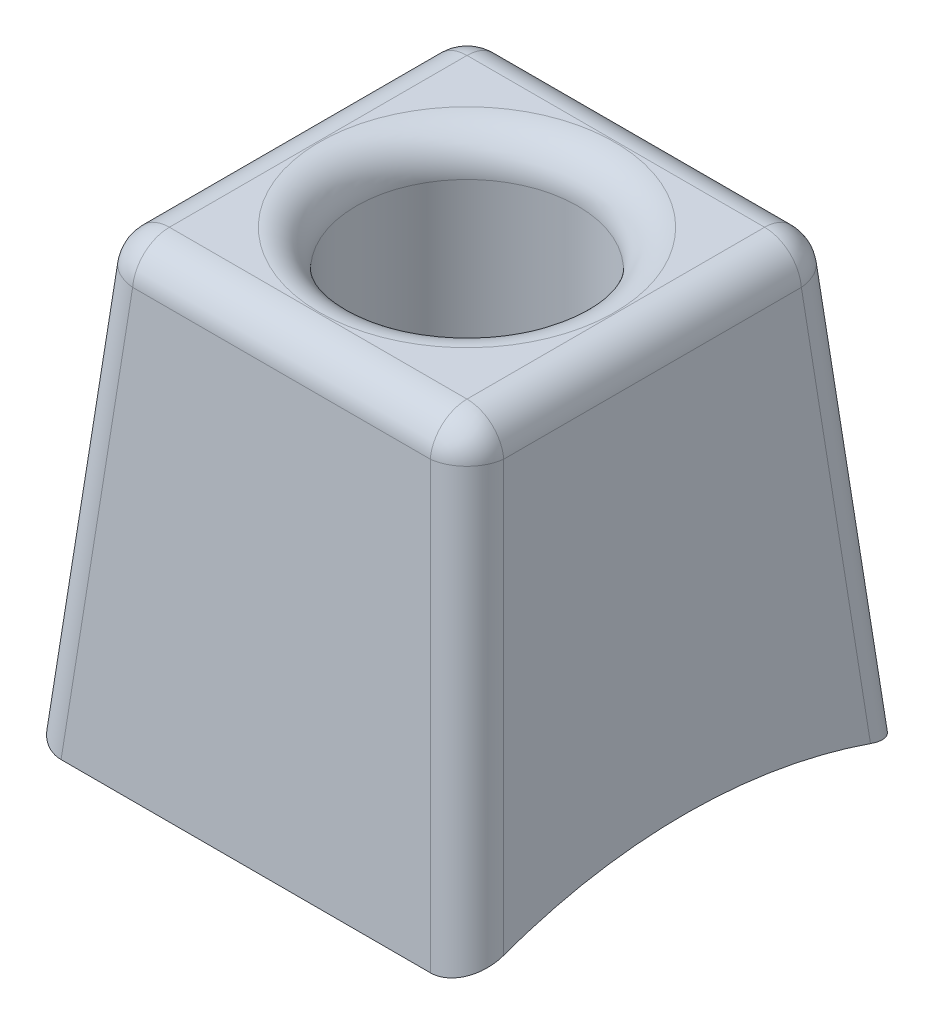
SolidWorks part; units mm, degrees
ref_plane "Front Plane" through (0, 0, 0) normal (0, 0, 1) x (1, 0, 0)
ref_plane "Top Plane" through (0, 0, 0) normal (0, 1, 0) x (1, 0, 0)
ref_plane "Right Plane" through (0, 0, 0) normal (1, 0, 0) x (0, 0, -1)
sketch "Sketch1" plane through (0, 0, 0) normal (0, 1, 0) x (1, 0, 0)
  line L1 (0, 0) -> (-12, 0)
  line L2 (0, 0) -> (0, 12)
  line L3 (0, 12) -> (-12, 12)
  line L4 (-12, 0) -> (-12, 12)
  dimension "D1" = 12
  dimension "D2" = 12
extrude "Boss-Extrude1" add sketch "Sketch1" along normal blind 12 draft 5
sketch "Sketch2" plane through (0, 12, 0) normal (0, 1, 0) x (1, 0, 0)
  line L0 (-10.9501, 6) -> (-1.0499, 6) construction
  line L1 (-10.9501, 10.9501) -> (-10.9501, 1.0499) construction
  line L2 (-1.0499, 1.0499) -> (-1.0499, 10.9501) construction
  line L3 (-6, 10.9501) -> (-6, 1.0499) construction
  line L4 (-1.0499, 10.9501) -> (-10.9501, 10.9501) construction
  line L5 (-10.9501, 1.0499) -> (-1.0499, 1.0499) construction
  circle A0 centre (-6, 6) radius 3
  dimension "D1" = 6
extrude "Cut-Extrude1" cut sketch "Sketch2" against normal through all
fillet "Fillet1" radius 1 9 edges at (-6, 12, -3) (-11.4751, 6, -11.4751) (-0.5249, 6, -11.4751) (-0.5249, 6, -0.5249) (-11.4751, 6, -0.5249) (-6, 12, -10.9501) (-10.9501, 12, -6) (-6, 12, -1.0499) (-1.0499, 12, -6)
sketch "Sketch3" plane through (0, 0, 0) normal (1, 0, 0) x (0, 0, -1)
  line L0 (6, 0) -> (6, 10.2816) construction
  line L1 (11.0038, 0) -> (0.9962, 0) construction
  line L2 (6, 0) -> (6, -8.6425) construction
  circle A0 centre (6, -14.8324) radius 16
  dimension "D1" = 32
extrude "Cut-Extrude2" cut sketch "Sketch3" against normal through all
